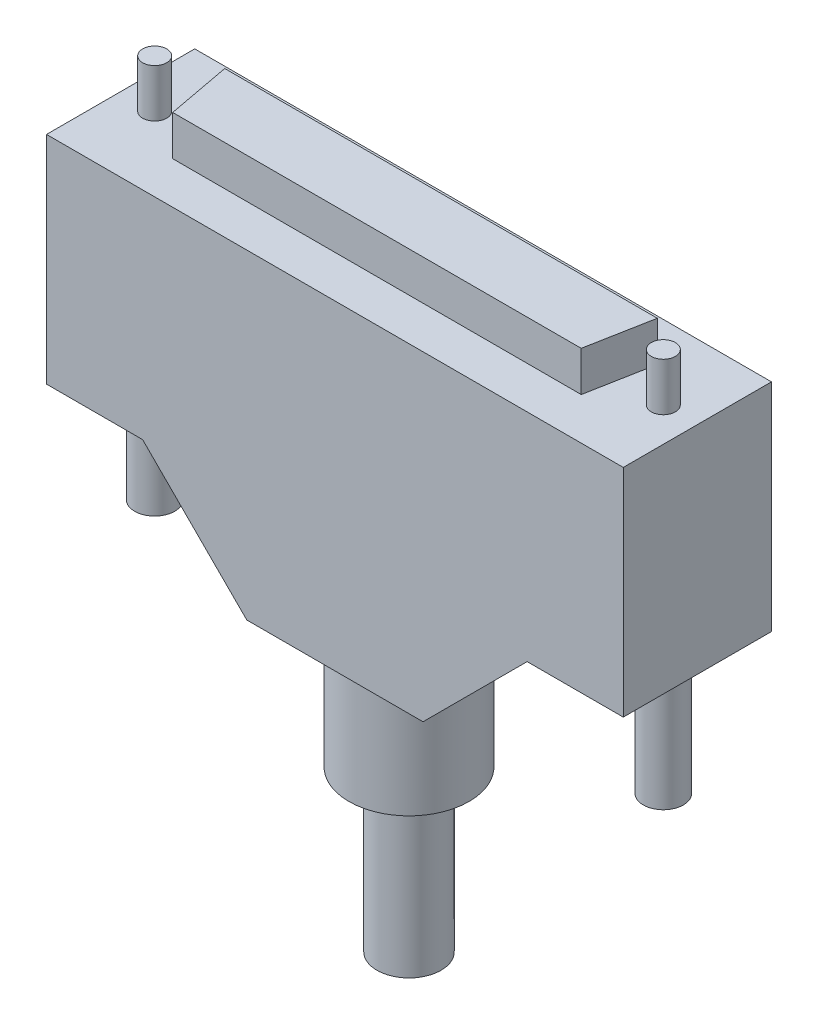
SolidWorks part; units mm, degrees
ref_plane "前视基准面" through (0, 0, 0) normal (0, 0, 1) x (1, 0, 0)
ref_plane "上视基准面" through (0, 0, 0) normal (0, 1, 0) x (1, 0, 0)
ref_plane "右视基准面" through (0, 0, 0) normal (1, 0, 0) x (0, 0, -1)
sketch "草图1" plane through (0, 0, 0) normal (0, 0, 1) x (1, 0, 0)
  line L0 (36, 0) -> (-36, 0)
  line L1 (-36, 0) -> (-36, -27)
  line L2 (-36, -27) -> (-24, -27)
  line L3 (-24, -27) -> (-11, -40)
  line L4 (-11, -40) -> (11, -40)
  line L5 (0, 0) -> (0, -40) construction
  line L6 (24, -27) -> (11, -40)
  line L7 (36, -27) -> (24, -27)
  line L8 (36, 0) -> (36, -27)
  dimension "D1" = 72
  dimension "D2" = 27
  dimension "D3" = 40
  dimension "D4" = 12
  dimension "D5" = 22
extrude "凸台-拉伸1" add sketch "草图1" along normal mid plane 18.5
sketch "草图2" plane through (0, -40, 0) normal (0, -1, 0) x (1, 0, 0)
  circle A0 centre (0, 0) radius 7.5
  dimension "D1" = 15
extrude "凸台-拉伸2" add sketch "草图2" along normal blind 15
sketch "草图3" plane through (0, -55, 0) normal (0, -1, 0) x (1, 0, 0)
  circle A0 centre (0, 0) radius 4
  dimension "D1" = 8
extrude "凸台-拉伸3" add sketch "草图3" along normal blind 20
sketch "草图4" plane through (0, -27, 0) normal (0, -1, 0) x (1, 0, 0)
  line L0 (0, 0) -> (0, 12.1196) construction
  line L1 (0, 0) -> (-31.75, 0) construction
  circle A0 centre (-31.75, 0) radius 2.5
  circle A1 centre (31.75, 0) radius 2.5
  dimension "D2" = 5
  dimension "D1" = 63.5
extrude "凸台-拉伸4" add sketch "草图4" along normal blind 15
sketch "草图5" plane through (0, 0, 0) normal (0, 1, 0) x (1, 0, 0)
  line L0 (-27, 4) -> (27, 4)
  line L1 (27, 4) -> (25.5, -4)
  line L2 (25.5, -4) -> (-25.5, -4)
  line L3 (-25.5, -4) -> (-27, 4)
  line L4 (0, 0) -> (0, 4) construction
  line L5 (0, 0) -> (18.119, 0) construction
  dimension "D1" = 54
  dimension "D2" = 51
  dimension "D3" = 8
extrude "凸台-拉伸5" add sketch "草图5" along normal blind 5
sketch "草图6" plane through (0, 0, 0) normal (0, 1, 0) x (1, 0, 0)
  line L0 (0, 0) -> (0, 10.8409) construction
  line L1 (0, 0) -> (-20.0503, 0) construction
  circle A0 centre (-31.75, 0) radius 1.5
  circle A1 centre (-31.75, 0) radius 2.5 construction
  circle A2 centre (31.75, 0) radius 1.5
  dimension "D1" = 3
extrude "凸台-拉伸6" add sketch "草图6" along normal blind 6
